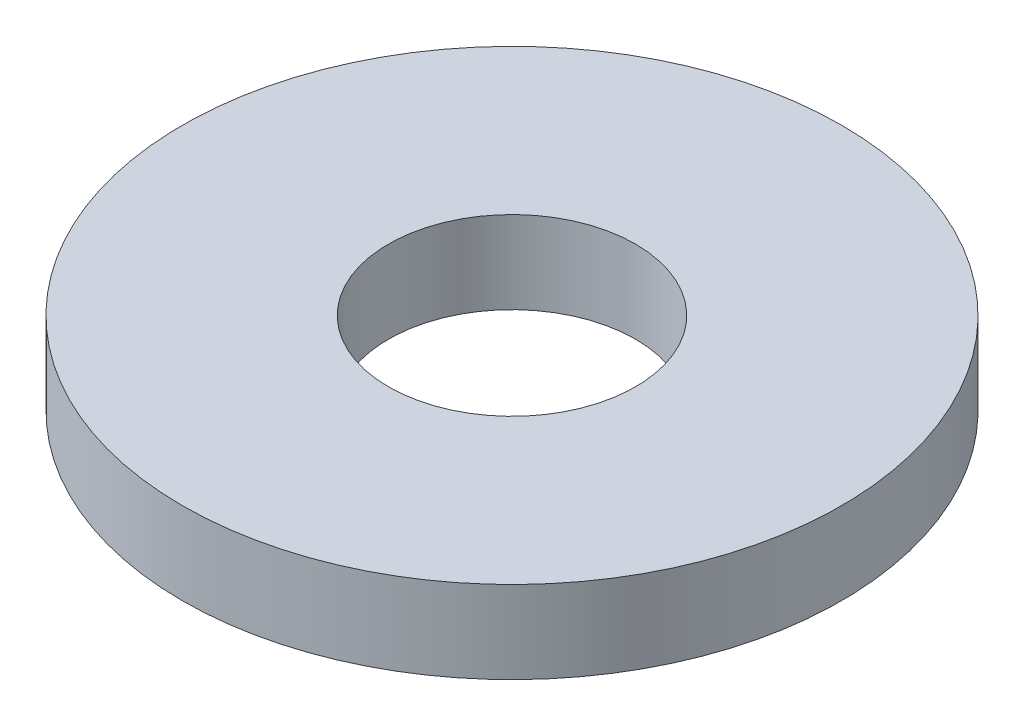
SolidWorks part; units mm, degrees
ref_plane "Ön Düzlem" through (0, 0, 0) normal (0, 0, 1) x (1, 0, 0)
ref_plane "Üst Düzlem" through (0, 0, 0) normal (0, 1, 0) x (1, 0, 0)
ref_plane "Sağ Düzlem" through (0, 0, 0) normal (1, 0, 0) x (0, 0, -1)
sketch "Çizim1" plane through (0, 0, 0) normal (0, 1, 0) x (1, 0, 0)
  circle A0 centre (0, 0) radius 1.5
  circle A1 centre (0, 0) radius 4
  dimension "D1" = 8
  dimension "D2" = 3
extrude "Yükseklik-Ekstrüzyon1" add sketch "Çizim1" along normal blind 1
